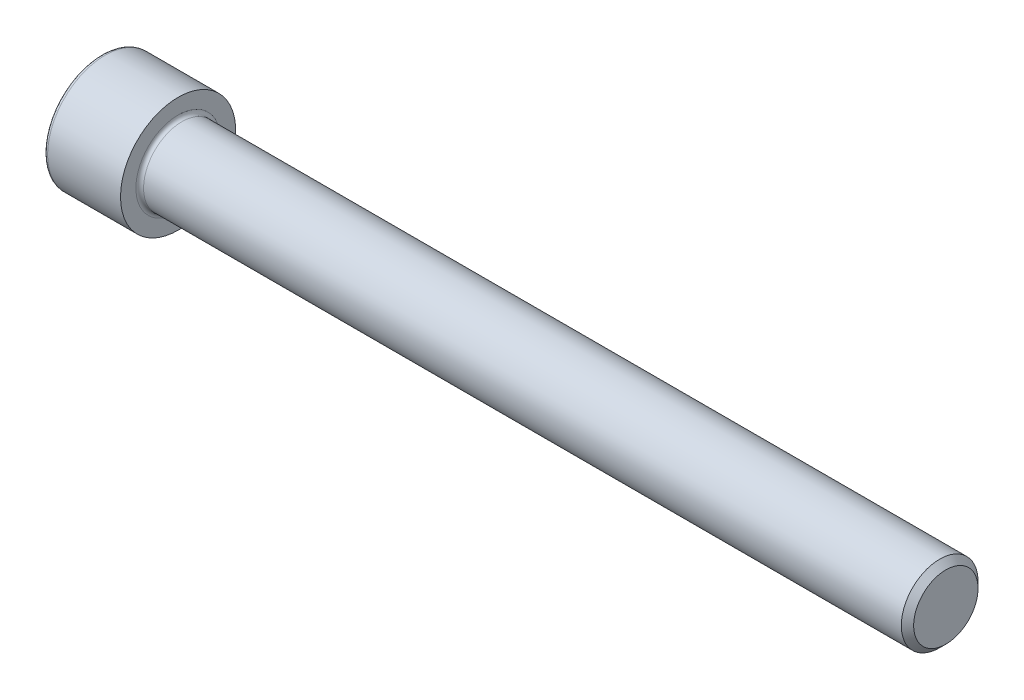
SolidWorks part; units mm, degrees
revolve "Base-Revolve" add sketch "BodySke"
sketch "BodySke" plane through (0, 0, 0) normal (0, 0, 1) x (1, 0, 0)
  line L0 (0, 0) -> (0, 9)
  line L1 (0, 9) -> (12, 9)
  line L2 (12, 9) -> (12, 6)
  line L3 (12, 6) -> (131.036, 6)
  line L4 (132, 5.036) -> (132, 0)
  line L5 (132, 0) -> (0, 0)
  line L6 (-31.75, 0) -> (127, 0) construction
  line L8 (132, 5.036) -> (131.036, 6)
  line L10 (132, -5.036) -> (131.036, -6) construction
  line L11 (13.75, 9.525) -> (13.75, 3.175) construction
  line L12 (96, 9.525) -> (96, 3.175) construction
  line L13 (72, 9.525) -> (72, 3.175) construction
  dimension "Body_ch_ang" = 45
  dimension "Thread_length" = 60
cosmetic thread "ThreadCosmetic" [suppressed]
fillet "Fillet1" radius 0.6 1 edges at (12, 0, 6)
fillet "Fillet2" radius 0.6 1 edges at (0, 0, 9)
ref_plane "Plane1" through (0, 0, 0) normal (0, 0, 1) x (1, 0, 0)
ref_plane "Plane2" through (0, 0, 0) normal (0, 1, 0) x (1, 0, 0)
ref_plane "Plane3" through (0, 0, 0) normal (1, 0, 0) x (0, 0, -1)
other "Configuration Table"
sketch "Sketch2" plane through (0, 0, 0) normal (0, 0, 1) x (1, 0, 0)
  line L0 (0, 5.0575) -> (6, 5.0575)
  line L1 (6, 5.0575) -> (8.9199, 0)
  line L2 (-31.75, 0) -> (127, 0) construction
  line L3 (8.9199, 0) -> (0, 0)
  line L4 (0, 0) -> (0, 5.0575)
  line L6 (0, 0) -> (47.625, 0) construction
  dimension "D2" = 60
revolve "Hex-PreBroach" cut sketch "Sketch2" angle 360 about L6
sketch "Sketch3" plane through (0, 0, 0) normal (-1, 0, 0) x (0, 0.5, 0.866)
  line L0 (2.9199, 5.0575) -> (-2.9199, 5.0575)
  line L1 (-2.9199, 5.0575) -> (-5.8399, 0)
  line L2 (2.9199, 5.0575) -> (5.8399, 0)
  line L3 (2.9199, -5.0575) -> (5.8399, 0)
  line L4 (2.9199, -5.0575) -> (-2.9199, -5.0575)
  line L5 (-2.9199, -5.0575) -> (-5.8399, 0)
extrude "Hex" cut sketch "Sketch3" against normal blind 6
sketch "ThdSchSke" plane through (0, 0, 0) normal (0, 0, 1) x (1, 0, 0)
  line L0 (96, -5.036) -> (95.325, -6)
  line L1 (96, -5.036) -> (96.675, -6)
  line L2 (96.675, -6) -> (96.675, -7.5)
  line L3 (-3.175, 0) -> (5.1513, 0) construction
  line L4 (0, 8.4) -> (0, -8.4) construction
  line L5 (96.675, -7.5) -> (95.325, -7.5)
  line L6 (95.325, -7.5) -> (95.325, -6)
revolve "ThreadSchematic" [suppressed] cut sketch "ThdSchSke" angle 360 about L3
pattern_linear "ThdSchPat" [suppressed]
equation "\"D2@Sketch3\" = \"Hex_size@Sketch3\" / 2"
equation "\"D1@Sketch3\" = \"Hex_size@Sketch3\" / 2"
equation "\"D1@Sketch2\" = \"Hex_size@Sketch3\" / 2"
equation "\"Thread_minor@ThreadCosmetic\"  =  \"Minor_dia@BodySke\""
equation "\"Depth@Sketch2\" =  \"Key_eng@Hex\""
equation "\"Thread_length@ThreadCosmetic\" = ((sgn( (\"Length@BodySke\" - \"Advance@BodySke\" * 3.0) - \"Thread_nom@BodySke\" )-1)*( (\"Length@BodySke\" - \"Advance@BodySke\" * 3.0) - \"Thread_nom@BodySke\" ))/-2+ \"Thread_nom@BodySke\""
equation "\"Thread_minor@ThdSchSke\" = \"Minor_dia@BodySke\""
equation "\"Diameter@ThdSchSke\" = \"Diameter@BodySke\""
equation "\"Overcut@ThdSchSke\" = \"Diameter@BodySke\" * 1.25"
equation "\"Start@ThdSchSke\" = \"Head_ht@BodySke\" + \"Length@BodySke\" - \"Thread_length@ThreadCosmetic\"  '---Non-countersunk---"
equation "\"Num_threads@ThdSchPat\" = int( \"Thread_length@ThreadCosmetic\" / \"Advance@BodySke\" + 0.999 )  + 1"
equation "\"Advance@ThdSchPat\" = \"Thread_length@ThreadCosmetic\" /  (\"Num_threads@ThdSchPat\" - 1) 'relax it"
equation "\"Num_threads@ThdSchPat\" = \"Num_threads@ThdSchPat\" - sgn( \"Num_threads@ThdSchPat\" - 1) '---chamfered tips only---"
